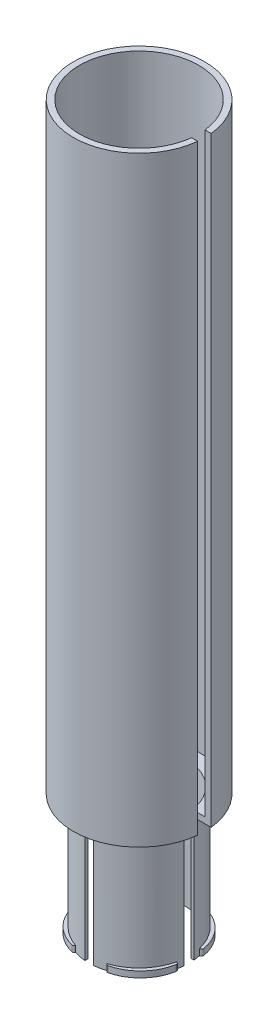
SolidWorks part; units mm, degrees
ref_plane "Front Plane" through (0, 0, 0) normal (0, 0, 1) x (1, 0, 0)
ref_plane "Top Plane" through (0, 0, 0) normal (0, 1, 0) x (1, 0, 0)
ref_plane "Right Plane" through (0, 0, 0) normal (1, 0, 0) x (0, 0, -1)
sketch "Sketch1" plane through (0, 0, 0) normal (0, 1, 0) x (1, 0, 0)
  line L5 (15.2664, 15.2664) -> (-15.2664, -15.2664) construction
  line L6 (15.2664, -15.2664) -> (-15.2664, 15.2664) construction
  circle A0 centre (0, 0) radius 21.59
  point P0 (0, 0)
  dimension "D1" = 43.18
extrude "Boss-Extrude1" add sketch "Sketch1" along normal blind 200
shell "Shell1" thickness 2
sketch "Sketch2" plane through (0, 0, 0) normal (1, 0, 0) x (0, 0, -1)
  line L0 (0, 19.558) -> (0, -19.558) construction
  line L2 (2.214, 104.2698) -> (2.214, 0)
  line L3 (2.214, 0) -> (-2.214, 0)
  line L4 (-2.214, 104.2698) -> (-2.214, 0)
  line L5 (2.214, 104.2698) -> (-2.214, 0) construction
  line L6 (2.214, 0) -> (-2.214, 104.2698) construction
  line L7 (19.558, 0) -> (-19.558, 0) construction
  line L10 (-2.214, 104.2698) -> (-2.214, 199.7944)
  line L11 (-2.214, 199.7944) -> (2.214, 199.7944)
  line L12 (2.214, 104.2698) -> (2.214, 199.7944)
  point P0 (0, 52.1349)
extrude "Cut-Extrude1" cut sketch "Sketch2" against normal mid plane 10 from offset 20
sketch "Sketch4" plane through (0, 0, 0) normal (0, -1, 0) x (1, 0, 0)
  circle A0 centre (0, 0) radius 16.5
  dimension "D1" = 33
extrude "Boss-Extrude2" add sketch "Sketch4" along normal blind 40
sketch "Sketch7" plane through (0, -40, 0) normal (0, -1, 0) x (-1, 0, 0)
  circle A0 centre (0, 0) radius 15.5
  dimension "D1" = 31
extrude "Cut-Extrude4" cut sketch "Sketch7" against normal blind 62
sketch "Sketch8" plane through (0, 0, 0) normal (0, 1, 0) x (1, 0, 0)
  line L0 (0, -19.558) -> (0, 19.558) construction
  line L1 (-1.3929, 23.0464) -> (1.3929, 23.0464)
  line L2 (-1.3929, 23.0464) -> (-1.3929, 17.1698)
  line L3 (-1.3929, 17.1698) -> (1.3929, 17.1698)
  line L4 (1.3929, 23.0464) -> (1.3929, 17.1698)
  line L5 (-1.3929, 23.0464) -> (1.3929, 17.1698) construction
  line L6 (-1.3929, 17.1698) -> (1.3929, 23.0464) construction
  line L7 (14.2708, 1.6027) -> (23.1489, 1.6027)
  line L8 (14.2708, 1.6027) -> (14.2708, -1.6047)
  line L9 (14.2708, -1.6047) -> (23.1489, -1.6047)
  line L10 (23.1489, 1.6027) -> (23.1489, -1.6047)
  line L11 (14.2708, 1.6027) -> (23.1489, -1.6047) construction
  line L12 (14.2708, -1.6047) -> (23.1489, 1.6027) construction
  line L13 (-1.3657, -14.1994) -> (1.3929, -14.1994)
  line L14 (-1.3657, -14.1994) -> (-1.3657, -22.705)
  line L15 (-1.3657, -22.705) -> (1.3929, -22.705)
  line L16 (1.3929, -14.1994) -> (1.3929, -22.705)
  line L17 (-1.3657, -14.1994) -> (1.3929, -22.705) construction
  line L18 (-1.3657, -22.705) -> (1.3929, -14.1994) construction
  line L19 (-14.2708, 1.6027) -> (-23.1489, 1.6027)
  line L20 (-23.1489, 1.6027) -> (-23.1489, -1.6047)
  line L21 (-14.2708, -1.6047) -> (-23.1489, -1.6047)
  line L22 (-14.2708, 1.6027) -> (-14.2708, -1.6047)
  point P0 (0, 20.1081)
  point P5 (18.7098, -0.001)
  point P10 (0.0136, -18.4522)
  point P21 (0, 0)
  point P22 (0, 18.7444)
  point P23 (0, 0)
  point P24 (0, 0)
  point P25 (-1.3657, -20.4516)
  point P26 (0, 0)
  point P27 (20.2126, -1.6047)
extrude "Cut-Extrude5" cut sketch "Sketch8" against normal through all
sketch "Sketch9" plane through (0, -40, 0) normal (0, -1, 0) x (1, 0, 0)
  line L0 (23.749, 0) -> (-23.749, 0) construction
  line L2 (0, -23.749) -> (0, 23.749) construction
  arc A0 (5.7778, 15.4553) -> (16.0773, 4.4501) centre (2.5628, 2.1243) cw construction
  arc A1 (16.7263, 4.5618) -> (5.9322, 16.0955) centre (2.5628, 2.1243) ccw
  arc A2 (15.4283, 4.3385) -> (5.6234, 14.8151) centre (2.5628, 2.1243) ccw
  arc A3 (15.4283, 4.3385) -> (16.7263, 4.5618) centre (16.0773, 4.4501) ccw
  arc A4 (5.9322, 16.0955) -> (5.6234, 14.8151) centre (5.7778, 15.4553) ccw
  arc A5 (5.7778, -15.4553) -> (16.0773, -4.4501) centre (2.5628, -2.1243) ccw construction
  arc A6 (16.7263, -4.5618) -> (5.9322, -16.0955) centre (2.5628, -2.1243) cw
  arc A7 (15.4283, -4.3385) -> (5.6234, -14.8151) centre (2.5628, -2.1243) cw
  arc A8 (15.4283, -4.3385) -> (16.7263, -4.5618) centre (16.0773, -4.4501) cw
  arc A9 (5.9322, -16.0955) -> (5.6234, -14.8151) centre (5.7778, -15.4553) cw
  arc A10 (-5.7778, -15.4553) -> (-16.0773, -4.4501) centre (-2.5628, -2.1243) cw construction
  arc A11 (-16.7263, -4.5618) -> (-5.9322, -16.0955) centre (-2.5628, -2.1243) ccw
  arc A12 (-15.4283, -4.3385) -> (-5.6234, -14.8151) centre (-2.5628, -2.1243) ccw
  arc A13 (-15.4283, -4.3385) -> (-16.7263, -4.5618) centre (-16.0773, -4.4501) ccw
  arc A14 (-5.9322, -16.0955) -> (-5.6234, -14.8151) centre (-5.7778, -15.4553) ccw
  arc A15 (-5.7778, 15.4553) -> (-16.0773, 4.4501) centre (-2.5628, 2.1243) ccw construction
  arc A16 (-16.7263, 4.5618) -> (-5.9322, 16.0955) centre (-2.5628, 2.1243) cw
  arc A17 (-15.4283, 4.3385) -> (-5.6234, 14.8151) centre (-2.5628, 2.1243) cw
  arc A18 (-15.4283, 4.3385) -> (-16.7263, 4.5618) centre (-16.0773, 4.4501) cw
  arc A19 (-5.9322, 16.0955) -> (-5.6234, 14.8151) centre (-5.7778, 15.4553) cw
  arc A20 (16.3508, 2.214) -> (1.3929, 16.4411) centre (0, 0) ccw construction
  point P3 (12.5752, 11.4947)
  point P15 (12.5752, -11.4947)
  point P23 (-12.5752, -11.4947)
  point P31 (-12.5752, 11.4947)
  point P36 (-6.2301, -17.5797)
  point P40 (-6.5855, 17.383)
  point P41 (-6.3662, 17.4702)
extrude "Boss-Extrude4" add sketch "Sketch9" against normal blind 2
sketch "Sketch10" plane through (0, 200, 0) normal (0, 1, 0) x (1, 0, 0)
  circle A0 centre (0, 0) radius 21.59
extrude "Cut-Extrude7" cut sketch "Sketch10" against normal mid plane 5
